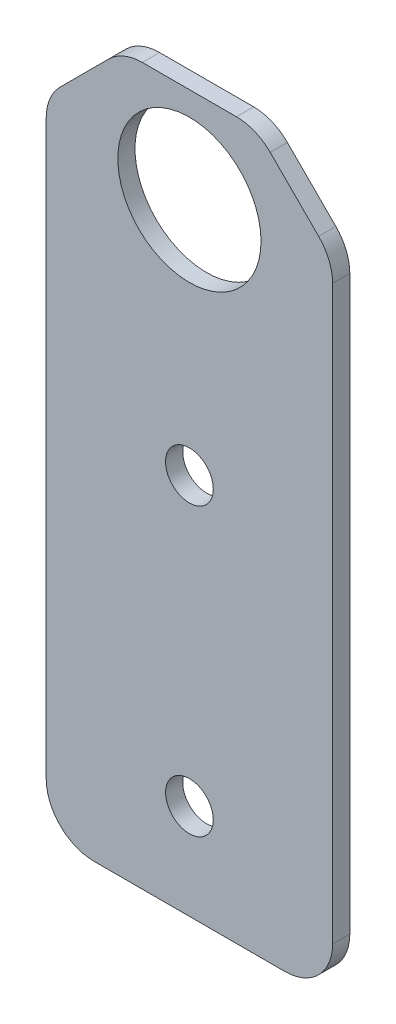
SolidWorks part; units mm, degrees
ref_plane "Front Plane" through (0, 0, 0) normal (0, 0, 1) x (1, 0, 0)
ref_plane "Top Plane" through (0, 0, 0) normal (0, 1, 0) x (1, 0, 0)
ref_plane "Right Plane" through (0, 0, 0) normal (1, 0, 0) x (0, 0, -1)
sketch "Sketch1" plane through (0, 0, 0) normal (0, 0, 1) x (1, 0, 0)
  line L0 (0, -31.75) -> (0, 6.35) construction
  line L1 (-19.05, 50.8) -> (19.05, 50.8)
  line L2 (-19.05, 50.8) -> (-19.05, -50.8)
  line L3 (-19.05, -50.8) -> (19.05, -50.8)
  line L4 (19.05, 50.8) -> (19.05, -50.8)
  line L5 (-19.05, 50.8) -> (19.05, -50.8) construction
  line L6 (-19.05, -50.8) -> (19.05, 50.8) construction
  line L8 (-19.05, -50.8) -> (19.05, -50.8) construction
  line L9 (-19.05, -50.8) -> (-19.05, 25.4) construction
  line L10 (-19.05, 25.4) -> (19.05, 25.4) construction
  line L11 (19.05, -50.8) -> (19.05, 25.4) construction
  circle A0 centre (0, -31.75) radius 3.175
  circle A1 centre (0, 6.35) radius 3.175
  circle A2 centre (0, 38.1) radius 9.525
  point P0 (0, 0)
  dimension "D5" = 19.05
  dimension "D8" = 6.35
  dimension "D1" = 101.6
  dimension "D2" = 38.1
  dimension "D3" = 38.1
  dimension "D4" = 19.05
  dimension "D6" = 12.7
  dimension "D7" = 76.2
  dimension "D9" = 19.05
extrude "Boss-Extrude1" add sketch "Sketch1" along normal mid plane 2.286
chamfer "Chamfer1" distance 10.16 angle 45 2 edges at (-19.05, 50.8, 0) (19.05, 50.8, 0)
fillet "Fillet1" radius 6.35 6 edges at (-19.05, -50.8, 0) (19.05, -50.8, 0) (19.05, 40.64, 0) (8.89, 50.8, 0) (-19.05, 40.64, 0) (-8.89, 50.8, 0)
sketch "Sketch2" plane through (0, 0, 1.143) normal (0, 0, 1) x (1, 0, 0)
  line L0 (-19.05, 38.0097) -> (-19.05, -44.45) construction
  line L1 (-19.05, -44.45) -> (19.05, -44.45)
  line L2 (-19.05, -44.45) -> (-19.05, -50.8)
  line L3 (-19.05, -50.8) -> (19.05, -50.8)
  line L4 (19.05, -44.45) -> (19.05, -50.8)
  line L5 (-12.7, -50.8) -> (12.7, -50.8) construction
  line L6 (19.05, -44.45) -> (19.05, 38.0097) construction
  dimension "D1" = 6.35
extrude "Cut-Extrude1" cut sketch "Sketch2" against normal through all
fillet "Fillet2" radius 6.35 2 edges at (19.05, -44.45, 0) (-19.05, -44.45, 0)
